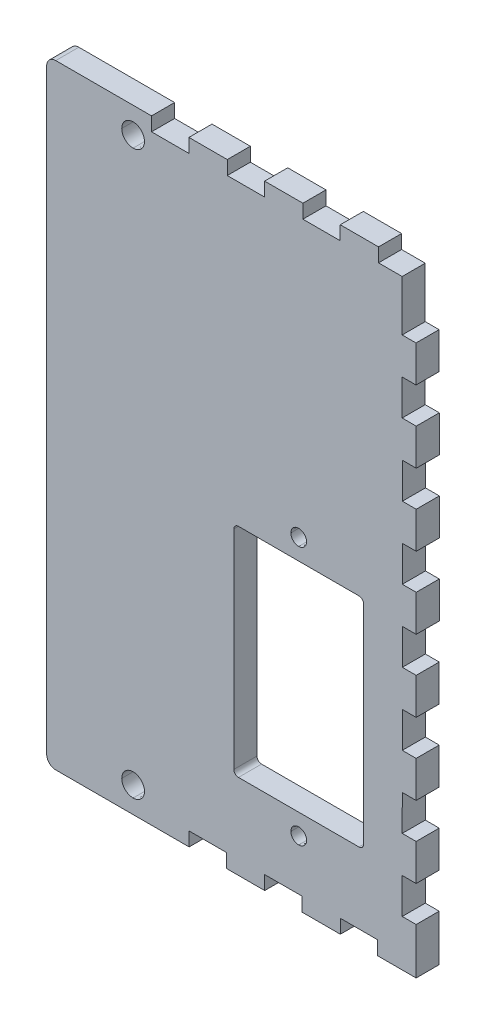
SolidWorks part; units mm, degrees
material "Perspex (TM) GS Acrylic Cast Sheet"
ref_plane "Front Plane" through (0, 0, 0) normal (0, 0, 1) x (1, 0, 0)
ref_plane "Top Plane" through (0, 0, 0) normal (0, 1, 0) x (1, 0, 0)
ref_plane "Right Plane" through (0, 0, 0) normal (1, 0, 0) x (0, 0, -1)
sketch "Sketch1" plane through (0, 0, 0) normal (0, 0, 1) x (1, 0, 0)
  line L0 (122.0197, 170.5106) -> (125.0355, 170.5106)
  line L1 (122.0099, 279.5901) -> (125.0099, 279.5901)
  line L2 (75.8686, 160.4748) -> (46.9739, 160.4748)
  line L3 (67.7181, 293.5476) -> (46.9739, 293.5476)
  line L4 (45.0099, 162.4388) -> (45.0099, 291.5836)
  line L5 (46.9739, 293.5476) -> (46.9739, 291.5836) construction
  line L6 (46.9739, 291.5836) -> (45.0099, 291.5836) construction
  line L7 (45.0099, 162.4388) -> (46.9739, 162.4388) construction
  line L8 (46.9739, 162.4388) -> (46.9739, 160.4748) construction
  line L9 (125.0591, 248.4266) -> (125.0591, 293.5584) construction
  line L1090 (86.5523, 178.8646) -> (112.6508, 178.8646)
  line L1091 (113.6527, 179.8644) -> (113.6527, 224.9646)
  line L1092 (112.6508, 225.9643) -> (86.5523, 225.9643)
  line L1093 (85.5504, 224.9646) -> (85.5504, 179.8644)
  line L1094 (125.0355, 160.4741) -> (125.0355, 170.5106)
  line L1096 (122.0197, 170.5106) -> (122.0197, 178.203)
  line L1097 (122.0197, 178.203) -> (125.0355, 178.2015)
  line L1098 (125.0355, 178.2015) -> (125.0355, 186.0924)
  line L1099 (122.0276, 186.094) -> (125.0355, 186.0924)
  line L1100 (122.0276, 186.094) -> (122.0315, 193.7849)
  line L1101 (122.0315, 193.7849) -> (125.0355, 193.7833)
  line L1102 (125.0355, 193.7833) -> (125.0355, 201.6739)
  line L1103 (122.0355, 201.6754) -> (125.0355, 201.6739)
  line L1104 (122.0355, 201.6754) -> (122.0394, 209.3663)
  line L1105 (122.0394, 209.3663) -> (125.0394, 209.3648)
  line L1106 (125.0394, 209.3648) -> (125.0434, 217.2557)
  line L1107 (122.0434, 217.2573) -> (125.0434, 217.2557)
  line L1108 (122.0434, 217.2573) -> (122.0472, 224.9482)
  line L1109 (122.0472, 224.9482) -> (125.0473, 224.9467)
  line L1110 (125.0473, 224.9467) -> (125.0513, 232.8376)
  line L1111 (122.0512, 232.8391) -> (125.0513, 232.8376)
  line L1112 (122.0512, 232.8391) -> (122.0551, 240.53)
  line L1113 (122.0551, 240.53) -> (125.0552, 240.5285)
  line L1114 (125.0552, 240.5285) -> (125.0591, 248.4266)
  line L1115 (122.0591, 248.4282) -> (125.0591, 248.4266)
  line L1116 (122.0591, 248.4282) -> (122.063, 256.1191)
  line L1117 (122.063, 256.1191) -> (125.0591, 256.1176)
  line L1118 (125.0591, 256.1176) -> (125.0591, 264.0133)
  line L1119 (122.0072, 264.0117) -> (125.0591, 264.0133)
  line L1120 (122.0072, 264.0117) -> (122.0072, 271.7042)
  line L1121 (122.0072, 271.7042) -> (125.0099, 271.7042)
  line L1122 (125.0099, 271.7042) -> (125.0099, 279.5901)
  line L1124 (122.0099, 279.5901) -> (122.0099, 290.5584)
  line L1125 (125.0355, 160.4741) -> (116.7102, 160.4741)
  line L1126 (116.7102, 163.4741) -> (116.7102, 160.4741)
  line L1127 (116.7102, 163.4741) -> (108.6193, 163.4741)
  line L1128 (108.6193, 163.4741) -> (108.6193, 160.4741)
  line L1129 (108.6193, 160.4741) -> (100.3284, 160.4741)
  line L1130 (100.3284, 163.4741) -> (100.3284, 160.4741)
  line L1131 (100.3284, 163.4741) -> (92.2375, 163.4741)
  line L1132 (92.2375, 163.4741) -> (92.2375, 160.4741)
  line L1133 (92.2375, 160.4741) -> (83.9466, 160.4741)
  line L1134 (83.9466, 163.4741) -> (83.9466, 160.4741)
  line L1135 (83.9466, 163.4741) -> (75.8686, 163.4741)
  line L1137 (122.0099, 290.5584) -> (116.89, 290.5584)
  line L1138 (116.89, 293.5584) -> (116.89, 290.5584)
  line L1139 (116.89, 293.5584) -> (108.5991, 293.5584)
  line L1140 (108.5991, 293.5584) -> (108.5993, 290.5584)
  line L1141 (108.5993, 290.5584) -> (100.5084, 290.5578)
  line L1142 (100.5081, 293.5578) -> (100.5084, 290.5578)
  line L1143 (100.5081, 293.5578) -> (92.2173, 293.5571)
  line L1144 (92.2173, 293.5571) -> (92.2175, 290.5571)
  line L1145 (92.2175, 290.5571) -> (84.1266, 290.5565)
  line L1146 (84.1263, 293.5565) -> (84.1266, 290.5565)
  line L1148 (75.8686, 163.4741) -> (75.8686, 160.4748)
  line L1154 (84.1263, 293.5565) -> (75.82, 293.5559)
  line L1155 (75.82, 293.5559) -> (75.8203, 290.5558)
  line L1156 (75.8203, 290.5558) -> (67.7184, 290.5552)
  line L1157 (67.7181, 293.5476) -> (67.7184, 290.5552)
  arc A0 (46.9739, 293.5476) -> (45.0099, 291.5836) centre (46.9739, 291.5836) ccw
  arc A1 (45.0099, 162.4388) -> (46.9739, 160.4748) centre (46.9739, 162.4388) ccw
  spline S182 degree 3 poles (85.5504, 179.8644) (85.5504, 179.3123) (85.9984, 178.8646) (86.5523, 178.8646) knots 0 0 0 0 1 1 1 1
  spline S183 degree 3 poles (112.6508, 178.8646) (113.2046, 178.8646) (113.6527, 179.3123) (113.6527, 179.8644) knots 0 0 0 0 1 1 1 1
  spline S184 degree 3 poles (113.6527, 224.9646) (113.6527, 225.5167) (113.2046, 225.9643) (112.6508, 225.9643) knots 0 0 0 0 1 1 1 1
  spline S185 degree 3 poles (86.5523, 225.9643) (85.9984, 225.9643) (85.5504, 225.5167) (85.5504, 224.9646) knots 0 0 0 0 1 1 1 1
  spline S186 degree 3 poles (97.9011, 230.4146) (97.9011, 229.4755) (98.6631, 228.7142) (99.6015, 228.7142) knots 0 0 0 0 1 1 1 1
  spline S187 degree 3 poles (99.6015, 228.7142) (100.5399, 228.7142) (101.3019, 229.4755) (101.3019, 230.4146) knots 0 0 0 0 1 1 1 1
  spline S188 degree 3 poles (101.3019, 230.4146) (101.3019, 231.3534) (100.5399, 232.1147) (99.6015, 232.1147) knots 0 0 0 0 1 1 1 1
  spline S189 degree 3 poles (99.6015, 232.1147) (98.6631, 232.1147) (97.9011, 231.3534) (97.9011, 230.4146) knots 0 0 0 0 1 1 1 1
  spline S190 degree 3 poles (97.9011, 174.4143) (97.9011, 173.4755) (98.6631, 172.7143) (99.6015, 172.7143) knots 0 0 0 0 1 1 1 1
  spline S191 degree 3 poles (99.6015, 172.7143) (100.5399, 172.7143) (101.3019, 173.4755) (101.3019, 174.4143) knots 0 0 0 0 1 1 1 1
  spline S192 degree 3 poles (101.3019, 174.4143) (101.3019, 175.3534) (100.5399, 176.1147) (99.6015, 176.1147) knots 0 0 0 0 1 1 1 1
  spline S193 degree 3 poles (99.6015, 176.1147) (98.6631, 176.1147) (97.9011, 175.3534) (97.9011, 174.4143) knots 0 0 0 0 1 1 1 1
  spline S194 degree 3 poles (61.268, 166.0501) (61.268, 164.6894) (62.3719, 163.5864) (63.7314, 163.5864) knots 0 0 0 0 1 1 1 1
  spline S195 degree 3 poles (63.7314, 163.5864) (65.0909, 163.5864) (66.1949, 164.6894) (66.1949, 166.0501) knots 0 0 0 0 1 1 1 1
  spline S196 degree 3 poles (66.1949, 166.0501) (66.1949, 167.4103) (65.0909, 168.5133) (63.7314, 168.5133) knots 0 0 0 0 1 1 1 1
  spline S197 degree 3 poles (63.7314, 168.5133) (62.3719, 168.5133) (61.268, 167.4103) (61.268, 166.0501) knots 0 0 0 0 1 1 1 1
  spline S198 degree 3 poles (61.268, 287.9701) (61.268, 286.6094) (62.3719, 285.5064) (63.7314, 285.5064) knots 0 0 0 0 1 1 1 1
  spline S199 degree 3 poles (63.7314, 285.5064) (65.0909, 285.5064) (66.1949, 286.6094) (66.1949, 287.9701) knots 0 0 0 0 1 1 1 1
  spline S200 degree 3 poles (66.1949, 287.9701) (66.1949, 289.3303) (65.0909, 290.4333) (63.7314, 290.4333) knots 0 0 0 0 1 1 1 1
  spline S201 degree 3 poles (63.7314, 290.4333) (62.3719, 290.4333) (61.268, 289.3303) (61.268, 287.9701) knots 0 0 0 0 1 1 1 1
  point P0 (45.5851, 292.9723)
  dimension "D2" = 1.964
  dimension "D1" = 7.8859
  dimension "D4" = 3
extrude "Boss-Extrude1" add sketch "Sketch1" along normal blind 5
